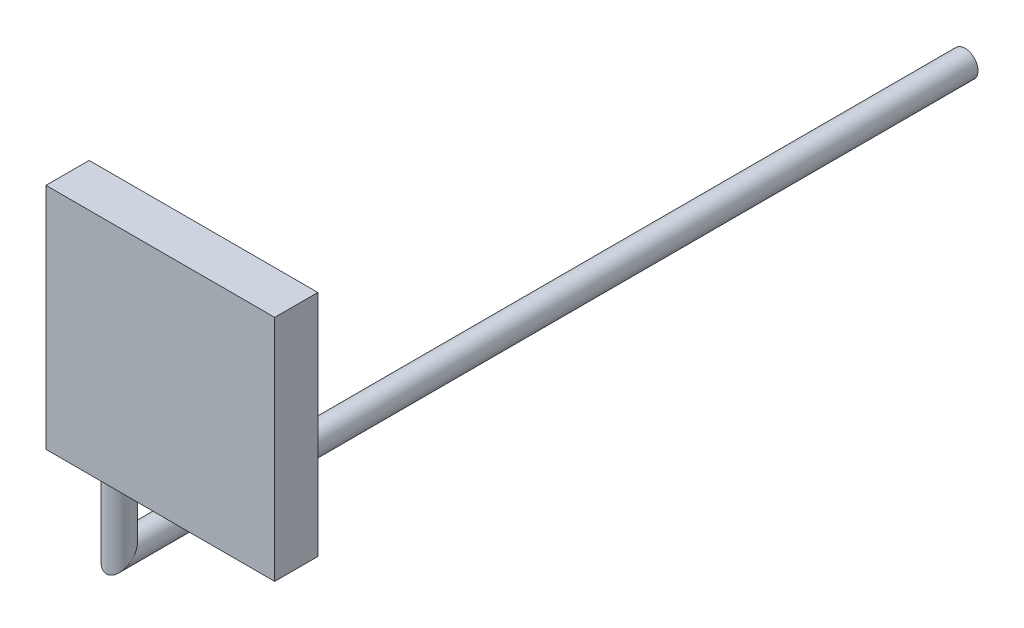
SolidWorks part; units mm, degrees
ref_plane "前视基准面" through (0, 0, 0) normal (0, 0, 1) x (1, 0, 0)
ref_plane "上视基准面" through (0, 0, 0) normal (0, 1, 0) x (1, 0, 0)
ref_plane "右视基准面" through (0, 0, 0) normal (1, 0, 0) x (0, 0, -1)
sketch "草图1" plane through (0, 0, 0) normal (0, 0, 1) x (1, 0, 0)
  line L0 (0, 0) -> (53, 0)
  line L1 (53, 0) -> (53, 53)
  line L2 (53, 53) -> (0, 53)
  line L3 (0, 53) -> (0, 0)
extrude "凸台-拉伸1" add sketch "草图1" along normal blind 10
sketch "草图2" plane through (0, 0, 0) normal (0, 1, 0) x (1, 0, 0)
  circle A0 centre (12, -5) radius 3
  point P2 (0, 0)
sketch "草图4" plane through (0, 0, 0) normal (1, 0, 0) x (0, 0, -1)
  line L0 (-5, 0) -> (-5, -17)
  line L1 (-2, 0) -> (-8, 0) construction
  line L2 (-5, -17) -> (191, -17)
sweep "扫描1" add profiles "草图2" path "草图4"
